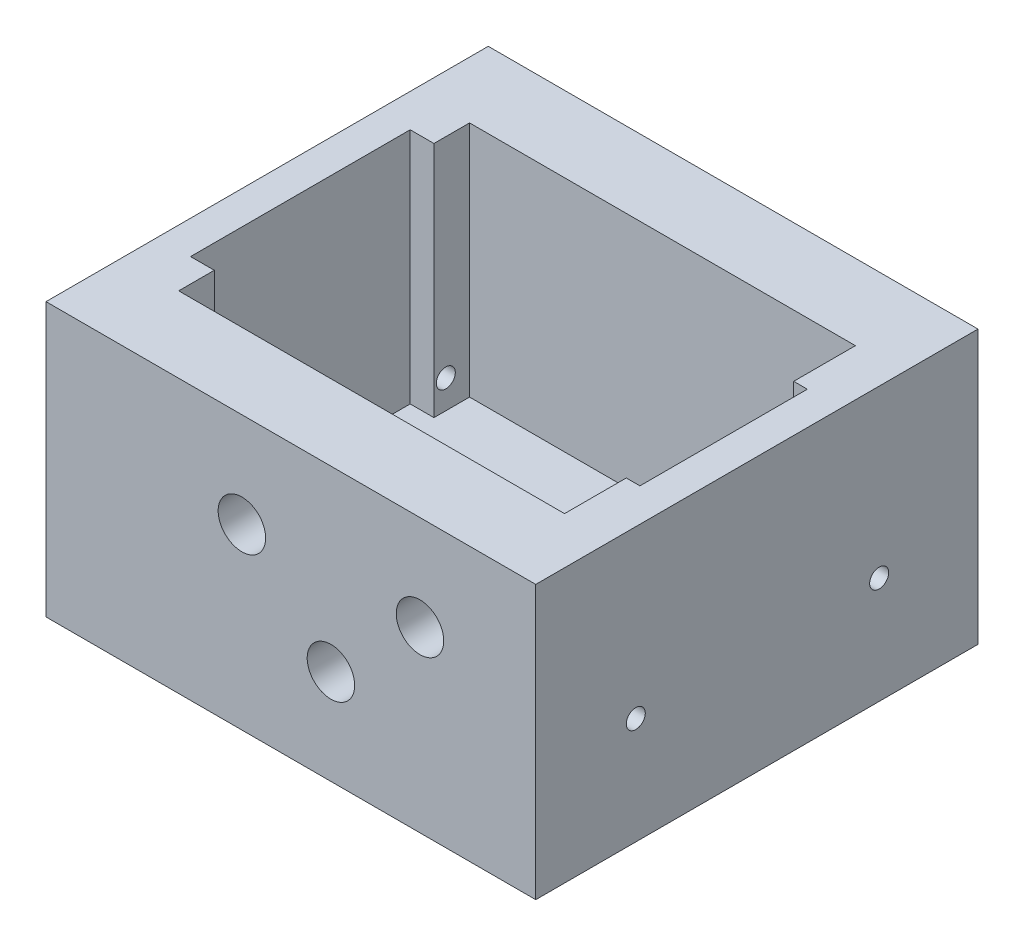
SolidWorks part; units mm, degrees
ref_plane "Front Plane" through (0, 0, 0) normal (0, 0, 1) x (1, 0, 0)
ref_plane "Top Plane" through (0, 0, 0) normal (0, 1, 0) x (1, 0, 0)
ref_plane "Right Plane" through (0, 0, 0) normal (1, 0, 0) x (0, 0, -1)
sketch "Sketch1" plane through (0, 0, 0) normal (0, 1, 0) x (1, 0, 0)
  line L1 (0, 0) -> (41.25, 0)
  line L2 (0, 0) -> (0, 37.25)
  line L3 (0, 37.25) -> (41.25, 37.25)
  line L4 (41.25, 0) -> (41.25, 37.25)
  dimension "D1" = 37.25
  dimension "D2" = 41.25
extrude "Boss-Extrude1" add sketch "Sketch1" along normal blind 23
sketch "Sketch2" plane through (0, 23, 0) normal (0, 1, 0) x (1, 0, 0)
  line L0 (22.5, 34.3711) -> (22.5, -3.2198) construction
  line L1 (0, 37.25) -> (0, 0) construction
  line L2 (37.3, 30.875) -> (4.8, 30.875)
  line L3 (4.8, 30.875) -> (4.8, 27.875)
  line L4 (4.8, 27.875) -> (2.8, 27.875)
  line L5 (2.8, 27.875) -> (2.8, 9.375)
  line L6 (2.8, 9.375) -> (4.8, 9.375)
  line L7 (4.8, 9.375) -> (4.8, 6.375)
  line L8 (4.8, 6.375) -> (37.3, 6.375)
  line L9 (37.3, 6.375) -> (37.3, 11.575)
  line L10 (37.3, 11.575) -> (38.45, 11.575)
  line L11 (38.45, 11.575) -> (38.45, 25.675)
  line L12 (38.45, 25.675) -> (37.3, 25.675)
  line L13 (37.3, 25.675) -> (37.3, 30.875)
  line L15 (0, 0) -> (41.25, 0) construction
  line L16 (41.25, 0) -> (41.25, 37.25) construction
  dimension "D1" = 22.5
  dimension "D2" = 1.15
  dimension "D3" = 32.5
  dimension "D4" = 3
  dimension "D5" = 18.5
  dimension "D6" = 5.2
  dimension "D7" = 14.1
  dimension "D8" = 2.8
  dimension "D9" = 2
  dimension "D10" = 2
  dimension "D11" = 6.375
  dimension "D12" = 3
extrude "Cut-Extrude1" cut sketch "Sketch2" against normal blind 20
sketch "Sketch3" plane through (37.3, 0, 0) normal (-1, 0, 0) x (0, 0, 1)
  line L3 (-11.575, 3) -> (-11.575, 23) construction
  line L4 (-11.575, 3) -> (-25.675, 3) construction
  line L5 (-25.675, 3) -> (-25.675, 23) construction
  line L6 (-11.575, 3) -> (-11.575, 23)
  line L7 (-11.575, 3) -> (-25.675, 3)
  line L8 (-25.675, 3) -> (-25.675, 23)
  circle A2 centre (-28.925, 9) radius 0.8
  circle A3 centre (-8.425, 9) radius 0.8
  dimension "D5" = 1.6
  dimension "D6" = 6
  dimension "D7" = 20.5
  dimension "D8" = 3.25
extrude "Cut-Extrude2" cut sketch "Sketch3" against normal up to surface (3.95 mm away) contours A2 | A3 up to face at (41.25, 11.5, -18.625)
sketch "Sketch4" plane through (4.8, 0, 0) normal (1, 0, 0) x (0, 0, -1)
  line L3 (27.875, 3) -> (27.875, 23) construction
  line L4 (27.875, 3) -> (9.375, 3) construction
  line L5 (9.375, 3) -> (9.375, 23) construction
  line L6 (27.875, 3) -> (27.875, 23)
  line L7 (27.875, 3) -> (9.375, 3)
  line L8 (9.375, 3) -> (9.375, 23)
  circle A2 centre (8.375, 5.4) radius 0.8
  circle A3 centre (28.875, 5.4) radius 0.8
  dimension "D5" = 1.6
  dimension "D6" = 20.5
  dimension "D7" = 1
  dimension "D8" = 2.4
extrude "Cut-Extrude3" cut sketch "Sketch4" against normal up to surface (4.8 mm away) contours A3 | A2 up to face at (0, 11.5, -18.625)
sketch "Sketch5" plane through (0, 0, 0) normal (0, 0, 1) x (1, 0, 0)
  line L0 (0, 23) -> (0, 0) construction
  line L1 (0, 0) -> (41.25, 0) construction
  circle A0 centre (16.5, 15) radius 2
  circle A1 centre (31.5, 15) radius 2
  circle A2 centre (24, 8) radius 2
  point P10 (0, 0)
  point P12 (19.9809, 11.358)
  dimension "D1" = 4
  dimension "D2" = 15
  dimension "D3" = 16.5
  dimension "D4" = 15
  dimension "D5" = 7
  dimension "D6" = 7.5
extrude "Cut-Extrude4" cut sketch "Sketch5" against normal blind 5.5
ref_plane "Plane1" through (0, 0, -18.625) normal (0, 0, 1) x (1, 0, 0)
mirror "Mirror1" about plane through (0, 0, -18.625) normal (0, 0, 1) of "Cut-Extrude4"
